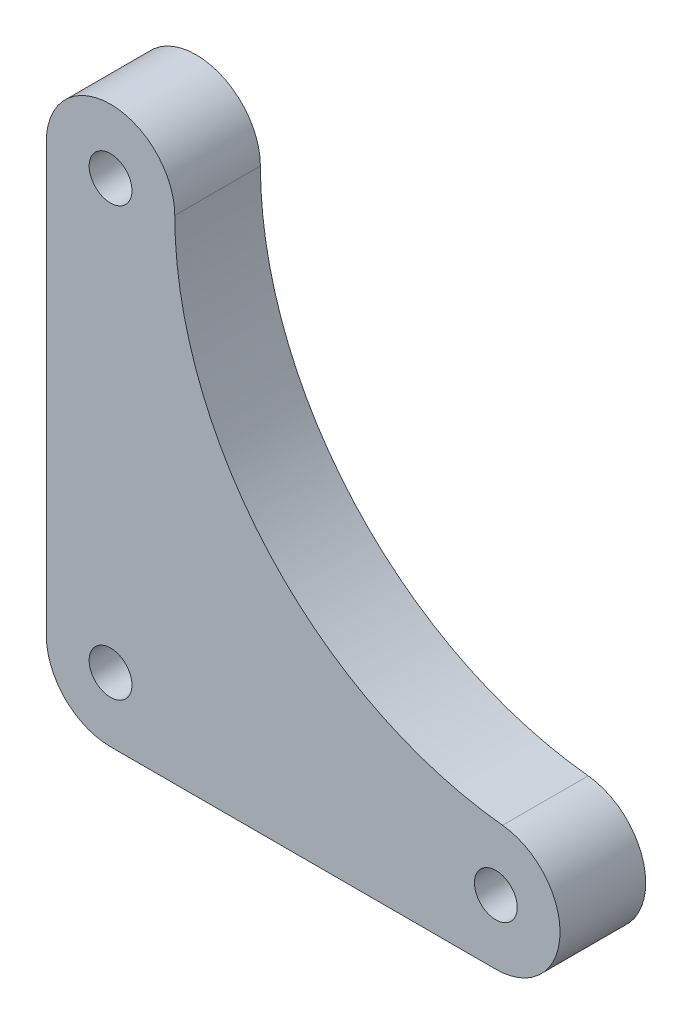
SolidWorks part; units mm, degrees
ref_plane "Front Plane" through (0, 0, 0) normal (0, 0, 1) x (1, 0, 0)
ref_plane "Top Plane" through (0, 0, 0) normal (0, 1, 0) x (1, 0, 0)
ref_plane "Right Plane" through (0, 0, 0) normal (1, 0, 0) x (0, 0, -1)
sketch "Sketch1" plane through (0, 0, 0) normal (0, 0, 1) x (1, 0, 0)
  line L0 (-7.5, 0) -> (-7.5, 50)
  line L1 (0, -7.5) -> (45, -7.5)
  circle A0 centre (0, 0) radius 2.5
  circle A1 centre (45, 0) radius 2.5
  circle A2 centre (0, 50) radius 2.5
  arc A3 (-7.5, 50) -> (7.5, 50) centre (0, 50) cw
  arc A4 (45.7873, 7.4586) -> (45, -7.5) centre (45, 0) cw
  arc A5 (-7.5, 0) -> (0, -7.5) centre (0, 0) ccw
  arc A6 (7.5, 50) -> (45.7873, 7.4586) centre (50.2778, 50) ccw
  dimension "D1" = 5
  dimension "D4" = 5
  dimension "D5" = 5
  dimension "D6" = 5
  dimension "D2" = 45
  dimension "D3" = 50
extrude "Boss-Extrude1" add sketch "Sketch1" along normal blind 10
